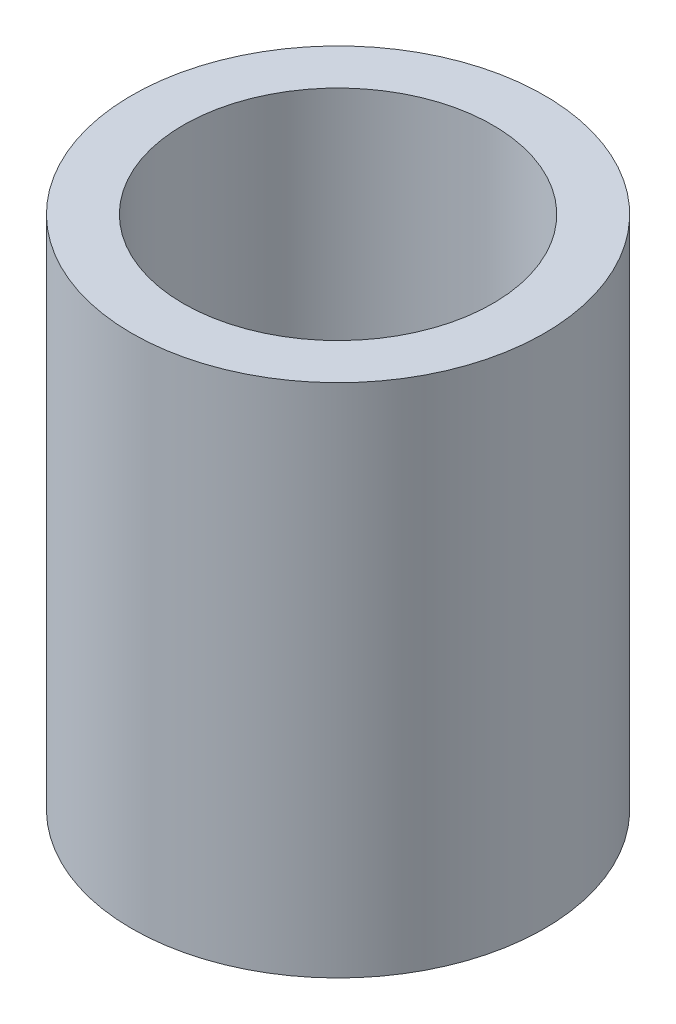
SolidWorks part; units mm, degrees
ref_plane "Plan de face" through (0, 0, 0) normal (0, 0, 1) x (1, 0, 0)
ref_plane "Plan de dessus" through (0, 0, 0) normal (0, 1, 0) x (1, 0, 0)
ref_plane "Plan de droite" through (0, 0, 0) normal (1, 0, 0) x (0, 0, -1)
sketch "Esquisse1" plane through (0, 0, 0) normal (0, 1, 0) x (1, 0, 0)
  circle A0 centre (0, 0) radius 6
  circle A1 centre (0, 0) radius 8
  dimension "D1" = 12
  dimension "D2" = 16
extrude "Boss.-Extru.1" add sketch "Esquisse1" along normal blind 20
